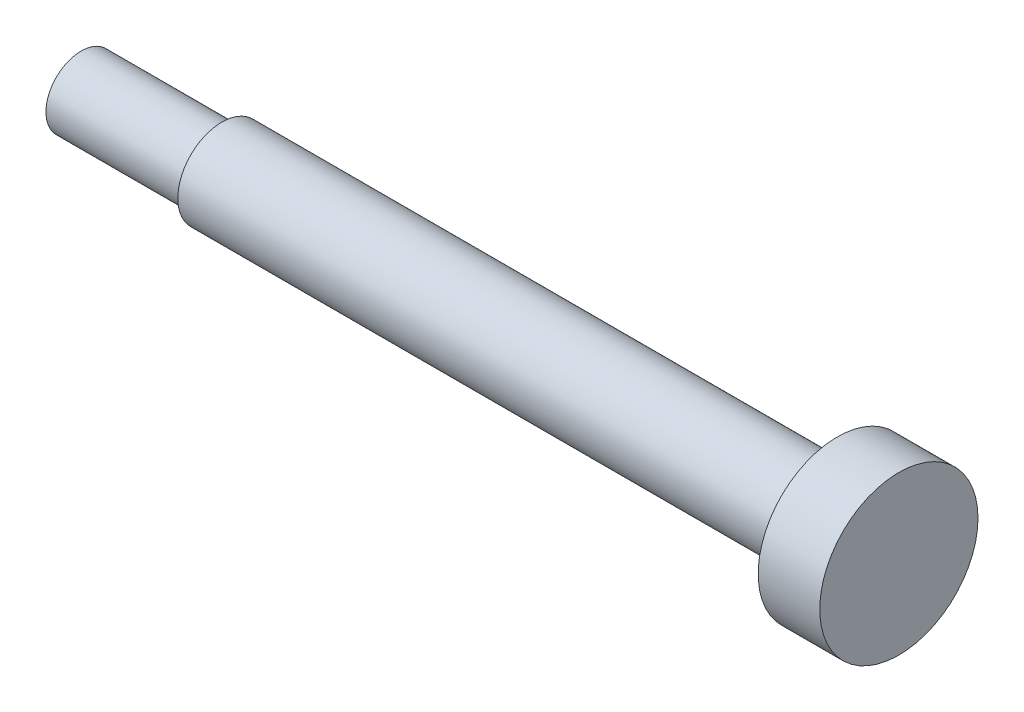
SolidWorks part; units mm, degrees
ref_plane "Front Plane" through (0, 0, 0) normal (0, 0, 1) x (1, 0, 0)
ref_plane "Top Plane" through (0, 0, 0) normal (0, 1, 0) x (1, 0, 0)
ref_plane "Right Plane" through (0, 0, 0) normal (1, 0, 0) x (0, 0, -1)
sketch "Sketch1" plane through (0, 0, 0) normal (0, 0, 1) x (1, 0, 0)
  line L0 (0, 0) -> (-43, 0) construction
  line L1 (3.5, 0) -> (3.5, 4.5)
  line L2 (3.5, 4.5) -> (0, 4.5)
  line L3 (0, 4.5) -> (0, 2.5)
  line L4 (0, 2.5) -> (-35, 2.5)
  line L5 (-35, 2.5) -> (-35, 2)
  line L6 (-35, 2) -> (-43, 2)
  line L7 (-43, 2) -> (-43, 0)
  line L8 (-43, 0) -> (3.5, 0)
  point P5 (-32.9632, 2.5)
  dimension "D1" = 43
  dimension "D2" = 8
  dimension "D3" = 3.5
  dimension "D4" = 4.5
  dimension "D5" = 2.5
  dimension "D6" = 2
revolve "Revolve1" add sketch "Sketch1" angle 360 about L0
